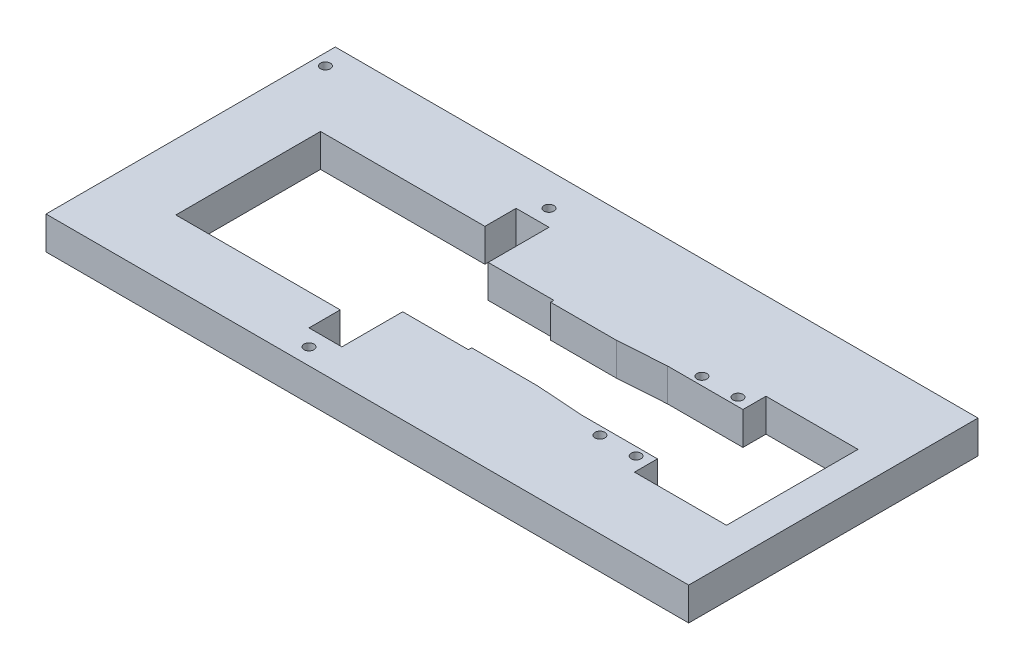
SolidWorks part; units mm, degrees
ref_plane "Спереди" through (0, 0, 0) normal (0, 0, 1) x (1, 0, 0)
ref_plane "Сверху" through (0, 0, 0) normal (0, 1, 0) x (1, 0, 0)
ref_plane "Справа" through (0, 0, 0) normal (1, 0, 0) x (0, 0, -1)
sketch "Эскиз1" plane through (0, 0, 0) normal (0, 1, 0) x (1, 0, 0)
  line L0 (0, 0) -> (53.9582, 0) construction
  line L1 (-5.5, 15.5) -> (5.5, 15.5) construction
  line L2 (-5.5, 15.5) -> (-5.5, -15.5) construction
  line L3 (-5.5, -15.5) -> (5.5, -15.5) construction
  line L4 (5.5, 15.5) -> (5.5, -15.5) construction
  line L5 (-5.5, 15.5) -> (5.5, -15.5) construction
  line L6 (-5.5, -15.5) -> (5.5, 15.5) construction
  line L7 (-13.5, 13) -> (-28, 12)
  line L8 (9.5, -20) -> (37.5, -20)
  line L9 (9.5, -20) -> (9.5, -13)
  line L10 (9.5, 20) -> (37.5, 20)
  line L11 (37.5, -20) -> (37.5, 20)
  line L12 (-73, 31.5) -> (-73, -31.5) construction
  line L14 (-13.5, -13) -> (9.5, -13)
  line L16 (-13.5, 13) -> (9.5, 13)
  line L18 (-28, 12) -> (-28, -12) construction
  line L19 (-13.5, 13) -> (-13.5, -13) construction
  line L20 (-28, -12) -> (-48, -12)
  line L22 (-28, 12) -> (-48, 12)
  line L23 (-48, -12) -> (-48, -13)
  line L26 (-13.5, -13) -> (-28, -12)
  line L27 (9.5, 13) -> (9.5, 20)
  line L28 (-48, 13) -> (-48, 12)
  line L29 (-48, -13) -> (-68, -13)
  line L31 (-48, 13) -> (-68, 13)
  line L34 (-148, -41.5) -> (47.5, -41.5)
  line L35 (-128, -22) -> (-78, -22)
  line L36 (-128, -22) -> (-128, 22)
  line L37 (-128, 22) -> (-78, 22)
  line L42 (-78, 22) -> (-78, 31.5)
  line L43 (-68, -31.5) -> (-78, -31.5)
  line L44 (-68, -31.5) -> (-68, -13)
  line L45 (-68, 31.5) -> (-78, 31.5)
  line L46 (-78, -31.5) -> (-78, -22)
  line L49 (-68, 13) -> (-68, 31.5)
  line L51 (-148, -41.5) -> (-148, 46.5)
  line L52 (-148, 46.5) -> (47.5, 46.5)
  line L53 (47.5, -41.5) -> (47.5, 46.5)
  circle A0 centre (-5.5, 15.5) radius 1.5
  circle A1 centre (5.5, 15.5) radius 1.5
  circle A2 centre (-5.5, -15.5) radius 1.5
  circle A3 centre (5.5, -15.5) radius 1.5
  circle A4 centre (-73, 36.5) radius 1.5
  circle A5 centre (-73, -36.5) radius 1.5
  circle A6 centre (-144.5, 40) radius 1.5
  point P0 (0, 0)
  point P13 (-73, 31.5)
  point P19 (0, 0)
  dimension "D4" = 150
  dimension "D5" = 40
  dimension "D6" = 3
  dimension "D27" = 28
  dimension "D33" = 3
  dimension "D34" = 3
  dimension "D1" = 31
  dimension "D2" = 11
  dimension "D7" = 4
  dimension "D8" = 23
  dimension "D9" = 13
  dimension "D10" = 13
  dimension "D11" = 14.5
  dimension "D12" = 20
  dimension "D13" = 12
  dimension "D14" = 12
  dimension "D15" = 10
  dimension "D16" = 13
  dimension "D17" = 13
  dimension "D18" = 20
  dimension "D19" = 10
  dimension "D20" = 50
  dimension "D21" = 22
  dimension "D22" = 22
  dimension "D23" = 31.5
  dimension "D24" = 31.5
  dimension "D25" = 15
  dimension "D26" = 20
  dimension "D28" = 20
  dimension "D29" = 20
  dimension "D30" = 10
  dimension "D31" = 5
  dimension "D32" = 5
extrude "Бобышка-Вытянуть1" add sketch "Эскиз1" along normal blind 10
